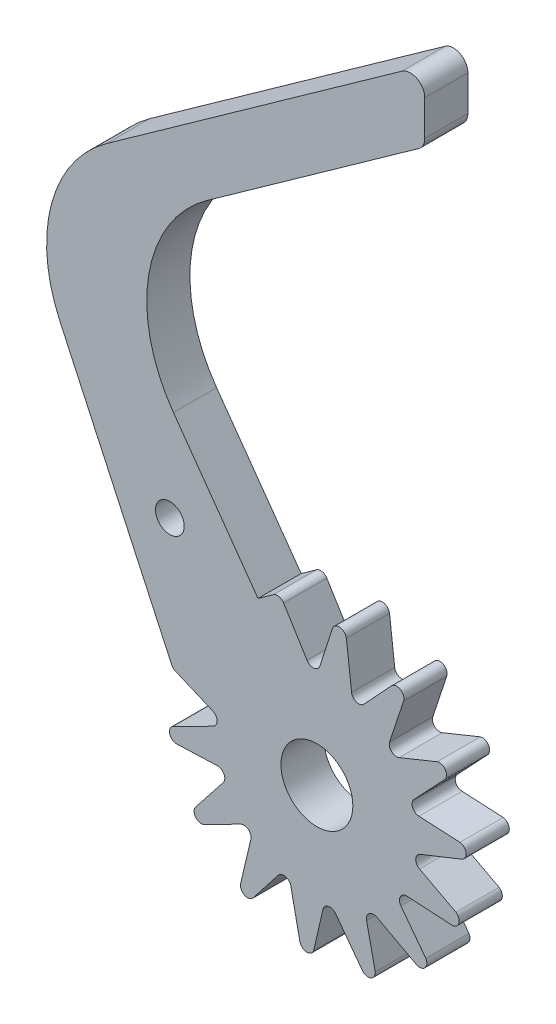
SolidWorks part; units mm, degrees
ref_plane "Piano frontale" through (0, 0, 0) normal (0, 0, 1) x (1, 0, 0)
ref_plane "Piano superiore" through (0, 0, 0) normal (0, 1, 0) x (1, 0, 0)
ref_plane "Piano destro" through (0, 0, 0) normal (1, 0, 0) x (0, 0, -1)
sketch "Sketch1" plane through (0, 0, 0) normal (0, 0, 1) x (1, 0, 0)
  line L0 (7.5, 44.629) -> (7.5, -25.7121) construction
  line L1 (0, 0) -> (-0.7189, 2.3944) construction
  line L2 (-15.7752, 25.5958) -> (7.5, 42.1736)
  line L3 (-21.3538, 26.5333) -> (-10.093, 2.1936)
  line L4 (-21.3538, 26.5333) -> (7.5, 47.0845)
  line L5 (0, 0) -> (-18.5645, 26.0645) construction
  line L6 (-18.5645, 26.0645) -> (7.5, 44.629) construction
  line L7 (-4.0951, 9.1969) -> (-15.7752, 25.5958)
  line L8 (7.5, 42.1736) -> (7.5, 47.0845)
  line L9 (1.629, 1.1603) -> (-15.7752, 25.5958) construction
  line L10 (-2.3127, 9.8123) -> (-0.6849, 7.1778)
  line L11 (-1.629, -1.1603) -> (-21.3538, 26.5333) construction
  line L12 (-1.7971, 5.986) -> (-3.2349, 10.7749) construction
  line L13 (2.0508, 9.8704) -> (2.4127, 6.7948)
  line L14 (1.095, 10.0097) -> (0.2163, 7.2871)
  line L15 (6.0301, 8.0789) -> (5.0583, 5.1385)
  line L16 (5.2227, 8.6091) -> (3.2756, 6.5129)
  line L17 (8.8794, 4.7735) -> (6.756, 2.5193)
  line L18 (8.3717, 5.5953) -> (5.7212, 4.5184)
  line L19 (10.0649, 0.5737) -> (7.1877, -0.5719)
  line L20 (9.952, 1.533) -> (7.0947, 1.6771)
  line L21 (9.3643, -3.7336) -> (6.2726, -3.556)
  line L22 (9.6674, -2.8165) -> (7.1388, -1.4784)
  line L23 (6.9091, -7.3414) -> (4.1821, -5.8737)
  line L24 (7.5714, -6.6383) -> (5.8452, -4.3568)
  line L25 (3.1591, -9.5734) -> (1.3079, -7.0908)
  line L26 (4.0565, -9.2161) -> (3.4562, -6.4189)
  line L27 (-1.1828, -10.0116) -> (-1.8113, -6.9792)
  line L28 (-0.2184, -10.067) -> (0.4197, -7.2782)
  line L29 (-5.303, -8.5737) -> (-4.5912, -5.5598)
  line L30 (-4.4525, -9.0315) -> (-2.6955, -6.7736)
  line L31 (-8.4296, -5.5293) -> (-6.5107, -3.0986)
  line L32 (-7.8522, -6.3036) -> (-5.3056, -4.9998)
  line L33 (-9.9766, -1.4487) -> (-7.2102, -0.0567)
  line L34 (-9.7805, -2.3945) -> (-6.9216, -2.2891)
  line L35 (-21.3538, 26.5333) -> (6.3397, 46.2581) construction
  line L36 (-9.8761, 1.9632) -> (-7.2405, 0.8505)
  line L37 (-4.0951, 9.1969) -> (-3.0282, 9.9568)
  line L38 (-15.7752, 25.5958) -> (8.6603, 43) construction
  line L39 (-9.7504, 2.9004) -> (-5.5356, 3.0263) [skipped]
  circle A0 centre (0, 0) radius 2.5
  arc A1 (1.095, 10.0097) -> (2.0508, 9.8704) centre (1.5543, 9.812) cw
  arc A4 (-3.0282, 9.9568) -> (-2.3127, 9.8123) centre (-2.7381, 9.5495) cw
  arc A5 (5.2227, 8.6091) -> (6.0301, 8.0789) centre (5.5553, 8.2358) cw
  arc A6 (8.3717, 5.5953) -> (8.8794, 4.7735) centre (8.5155, 5.1164) cw
  arc A7 (9.952, 1.533) -> (10.0649, 0.5737) centre (9.8799, 1.0382) cw
  arc A8 (9.6674, -2.8165) -> (9.3643, -3.7336) centre (9.393, -3.2345) cw
  arc A9 (7.5714, -6.6383) -> (6.9091, -7.3414) centre (7.146, -6.9011) cw
  arc A10 (4.0565, -9.2161) -> (3.1591, -9.5734) centre (3.56, -9.2745) cw
  arc A11 (-0.2184, -10.067) -> (-1.1828, -10.0116) centre (-0.6932, -9.9101) cw
  arc A12 (-4.4525, -9.0315) -> (-5.303, -8.5737) centre (-4.8164, -8.6886) cw
  arc A13 (-7.8522, -6.3036) -> (-8.4296, -5.5293) centre (-8.0371, -5.8391) cw
  arc A14 (-9.7805, -2.3945) -> (-9.9766, -1.4487) centre (-9.7518, -1.8954) cw
  arc A15 (-9.8761, 1.9632) -> (-10.093, 2.1936) centre (-9.6392, 2.4035) cw
  arc A16 (4.1821, -5.8737) -> (3.4562, -6.4189) centre (3.9451, -6.314) ccw
  arc A17 (1.3079, -7.0908) -> (0.4197, -7.2782) centre (0.9071, -7.3897) ccw
  arc A18 (-1.8113, -6.9792) -> (-2.6955, -6.7736) centre (-2.3009, -7.0807) ccw
  arc A19 (-4.5912, -5.5598) -> (-5.3056, -4.9998) centre (-5.0778, -5.4449) ccw
  arc A20 (-6.5107, -3.0986) -> (-6.9216, -2.2891) centre (-6.9031, -2.7888) ccw
  arc A21 (-7.2102, -0.0567) -> (-7.2405, 0.8505) centre (-7.4349, 0.3899) ccw
  arc A22 (6.2726, -3.556) -> (5.8452, -4.3568) centre (6.2439, -4.0551) ccw
  arc A23 (7.1388, -1.4784) -> (7.1877, -0.5719) centre (7.3727, -1.0364) cw
  arc A24 (7.0947, 1.6771) -> (6.756, 2.5193) centre (7.1199, 2.1765) cw
  arc A25 (5.7212, 4.5184) -> (5.0583, 5.1385) centre (5.533, 4.9816) cw
  arc A26 (2.4127, 6.7948) -> (3.2756, 6.5129) centre (2.9093, 6.8532) ccw
  arc A27 (0.2163, 7.2871) -> (-0.6849, 7.1778) centre (-0.2596, 7.4406) cw
  point P6 (3.3337, -0.8601)
  point P10 (-11.9867, 17.3861)
  point P76 (0, 0)
  point P89 (0, 0)
  dimension "D2" = 15
  dimension "D3" = 5
  dimension "D10" = 0.5
  dimension "D12" = 0.5
  dimension "D6" = 2
  dimension "D4" = 32
  dimension "D8" = 15
  dimension "D11" = 13
extrude "Boss-Extrude1" add sketch "Sketch1" along normal blind 3
fillet "Fillet1" radius 10 2 edges at (-21.3538, 26.5333, 1.5) (-15.7752, 25.5958, 1.5)
fillet "Fillet2" radius 1 2 edges at (7.5, 42.1736, 1.5) (7.5, 47.0845, 1.5)
sketch "Sketch2" plane through (0, 0, 3) normal (0, 0, 1) x (1, 0, 0)
  line L0 (0, 0) -> (-10.2245, 10.9754) construction
  line L1 (-4.0951, 9.1969) -> (-9.9738, 17.4506) construction
  line L2 (-4.0951, 9.1969) -> (-9.9738, 17.4506) construction
  line L3 (-17.8698, 19.0028) -> (-10.093, 2.1936) construction
  line L4 (-17.8698, 19.0028) -> (-10.093, 2.1936) construction
  arc A0 (-6.9954, 13.2689) -> (-12.7408, 7.9166) centre (0, 0) ccw construction
  circle A1 centre (-10.2245, 10.9754) radius 1
  point P11 (-10.2245, 10.9754)
  dimension "D1" = 2
extrude "Cut-Extrude1" cut sketch "Sketch2" against normal blind 5
sketch "Sketch3" plane through (0, 0, 3) normal (0, 0, 1) x (1, 0, 0)
  circle A0 centre (0, 0) radius 5
  circle A1 centre (0, 0) radius 1
